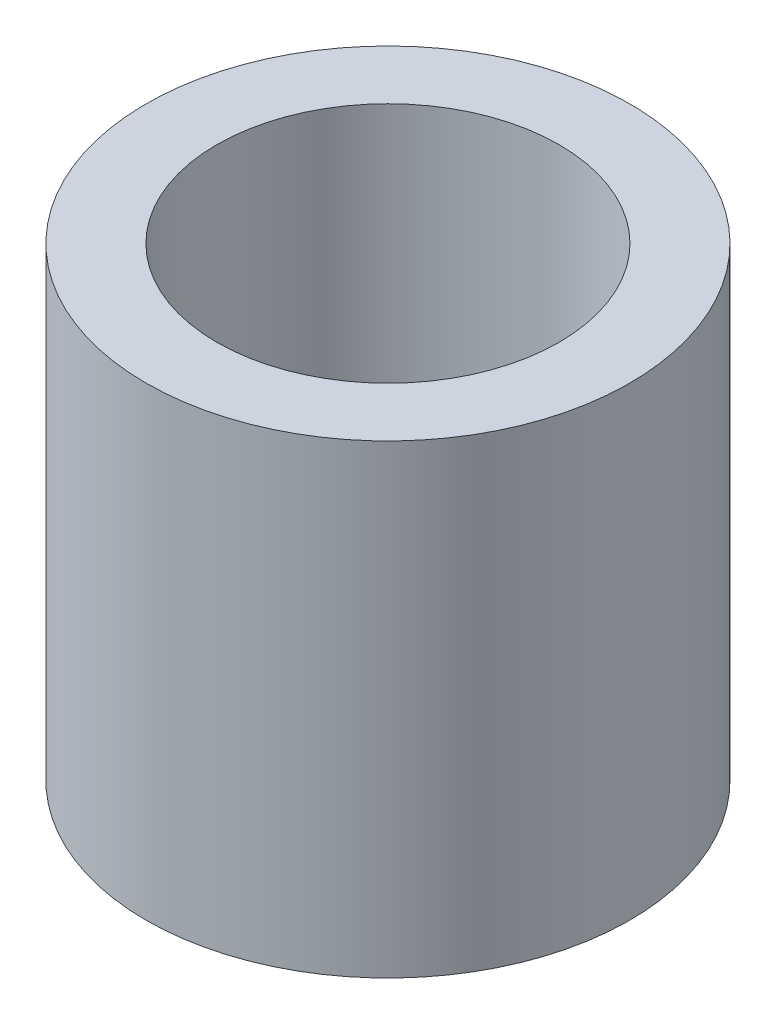
SolidWorks part; units mm, degrees
ref_plane "Front Plane" through (0, 0, 0) normal (0, 0, 1) x (1, 0, 0)
ref_plane "Top Plane" through (0, 0, 0) normal (0, 1, 0) x (1, 0, 0)
ref_plane "Right Plane" through (0, 0, 0) normal (1, 0, 0) x (0, 0, -1)
sketch "Sketch1" plane through (0, 0, 0) normal (0, 1, 0) x (1, 0, 0)
  circle A0 centre (0, 0) radius 1.651
  circle A1 centre (0, 0) radius 1.1684
  dimension "D1" = 3.302
  dimension "D2" = 2.3368
extrude "Boss-Extrude1" add sketch "Sketch1" along normal blind 3.175
